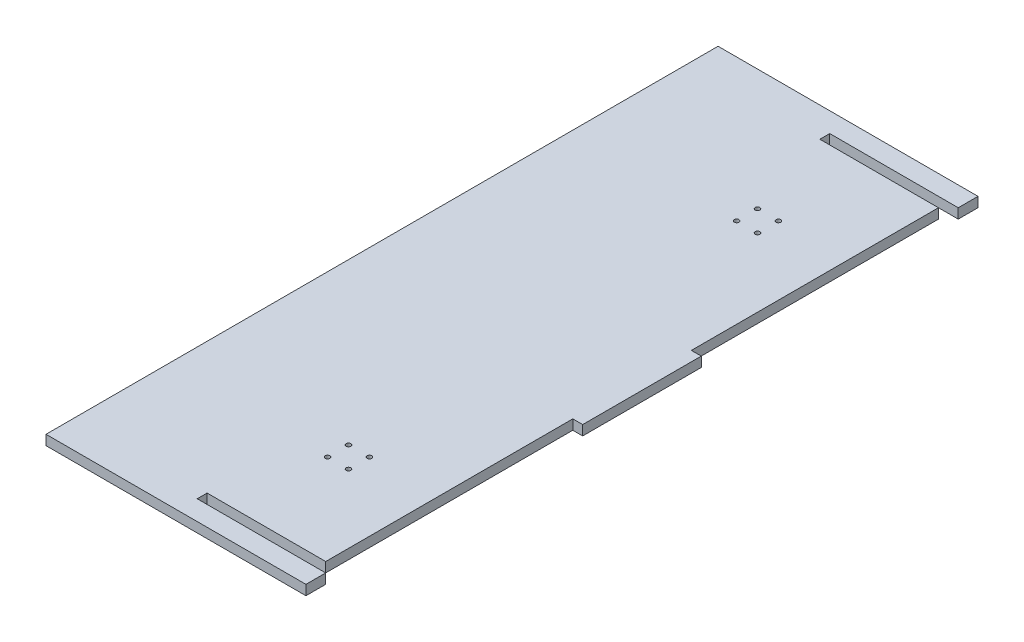
SolidWorks part; units mm, degrees
ref_plane "Front Plane" through (0, 0, 0) normal (0, 0, 1) x (1, 0, 0)
ref_plane "Top Plane" through (0, 0, 0) normal (0, 1, 0) x (1, 0, 0)
ref_plane "Right Plane" through (0, 0, 0) normal (1, 0, 0) x (0, 0, -1)
sketch "Sketch2" plane through (0, 0, 0) normal (0, 1, 0) x (1, 0, 0)
  line L1 (-83.5025, 215.9) -> (83.5025, 215.9)
  line L2 (-83.5025, 215.9) -> (-83.5025, -215.9)
  line L3 (-83.5025, -215.9) -> (83.5025, -215.9)
  line L4 (83.5025, 215.9) -> (83.5025, -215.9)
  line L5 (-83.5025, 215.9) -> (83.5025, -215.9) construction
  line L6 (-83.5025, -215.9) -> (83.5025, 215.9) construction
  point P0 (0, 0)
  dimension "D1" = 431.8
  dimension "D2" = 167.005
extrude "Boss-Extrude2" add sketch "Sketch2" along normal mid plane 6.35
sketch "Sketch3" plane through (0, 3.175, 0) normal (0, 1, 0) x (1, 0, 0)
  line L0 (83.5025, -215.9) -> (83.5025, 215.9) construction
  line L1 (83.5025, 196.85) -> (77.1525, 196.85)
  line L2 (83.5025, 196.85) -> (83.5025, -196.85)
  line L3 (83.5025, -196.85) -> (77.1525, -196.85)
  line L4 (77.1525, 196.85) -> (77.1525, -196.85)
  line L5 (83.5025, 215.9) -> (-83.5025, 215.9) construction
  point P8 (77.1525, 0)
  dimension "D1" = 6.35
  dimension "D2" = 19.05
extrude "Cut-Extrude1" cut sketch "Sketch3" against normal through all
sketch "Sketch4" plane through (0, 3.175, 0) normal (0, 1, 0) x (1, 0, 0)
  line L0 (-83.5025, 215.9) -> (-83.5025, -215.9) construction
  line L1 (-83.5025, 190.5) -> (-98.4758, 190.5)
  line L2 (-83.5025, 190.5) -> (-83.5025, -196.85)
  line L3 (-83.5025, -196.85) -> (-98.4758, -196.85)
  line L4 (-98.4758, 190.5) -> (-98.4758, -196.85)
  line L6 (83.5025, 215.9) -> (-83.5025, 215.9) construction
  line L7 (-83.5025, -215.9) -> (83.5025, -215.9) construction
  dimension "D1" = 14.9733
  dimension "D2" = 25.4
  dimension "D3" = 19.05
sketch "Sketch5" plane through (0, 3.175, 0) normal (0, 1, 0) x (1, 0, 0)
  line L1 (-32.7025, 203.2) -> (-83.5025, 203.2)
  line L2 (-32.7025, 203.2) -> (-32.7025, 196.85)
  line L3 (-32.7025, 196.85) -> (-83.5025, 196.85)
  line L4 (-83.5025, 203.2) -> (-83.5025, 196.85)
  line L5 (-83.5025, 215.9) -> (-83.5025, -215.9) construction
  line L7 (-83.5025, 215.9) -> (-83.5025, -215.9) construction
  line L8 (-83.5025, -203.2) -> (-32.7025, -203.2)
  line L9 (-83.5025, -203.2) -> (-83.5025, -196.85)
  line L10 (-83.5025, -196.85) -> (-32.7025, -196.85)
  line L11 (-32.7025, -203.2) -> (-32.7025, -196.85)
  line L13 (83.5025, 215.9) -> (-83.5025, 215.9) construction
  line L14 (-83.5025, -215.9) -> (83.5025, -215.9) construction
  dimension "D1" = 6.35
  dimension "D2" = 50.8
  dimension "D3" = 50.8
  dimension "D4" = 6.35
  dimension "D5" = 12.7
  dimension "D6" = 12.7
extrude "Cut-Extrude2" [suppressed] cut sketch "Sketch5" against normal through all
sketch "Sketch6" plane through (0, 3.175, 0) normal (0, 1, 0) x (1, 0, 0)
  line L0 (19.635, -124.6775) -> (33.07, -124.6775) construction
  line L1 (33.07, -124.6775) -> (33.07, -138.1125) construction
  line L2 (33.07, -138.1125) -> (19.635, -138.1125) construction
  line L3 (19.635, -138.1125) -> (19.635, -124.6775) construction
  line L4 (77.1525, 196.85) -> (77.1525, -196.85) construction
  circle A0 centre (19.635, -124.6775) radius 1.5
  circle A1 centre (19.635, -138.1125) radius 1.5
  circle A2 centre (33.07, -124.6775) radius 1.5
  circle A3 centre (33.07, -138.1125) radius 1.5
  point P10 (26.3525, -124.6775)
  dimension "D1" = 3
  dimension "D2" = 19
  dimension "D3" = 138.1125
  dimension "D4" = 50.8
extrude "Cut-Extrude3" cut sketch "Sketch6" against normal through all
mirror "Mirror1" about plane through (0, 0, 0) normal (0, 0, 1) of "Cut-Extrude3"
sketch "Sketch7" plane through (0, 3.175, 0) normal (0, 1, 0) x (1, 0, 0)
  line L1 (83.5025, 203.2) -> (0.9525, 203.2)
  line L2 (83.5025, 203.2) -> (83.5025, 196.85)
  line L3 (83.5025, 196.85) -> (0.9525, 196.85)
  line L4 (0.9525, 203.2) -> (0.9525, 196.85)
  line L5 (83.5025, -203.2) -> (0.9525, -203.2)
  line L6 (83.5025, -203.2) -> (83.5025, -196.85)
  line L7 (83.5025, -196.85) -> (0.9525, -196.85)
  line L8 (0.9525, -203.2) -> (0.9525, -196.85)
  dimension "D1" = 82.55
  dimension "D2" = 6.35
extrude "Cut-Extrude4" cut sketch "Sketch7" against normal through all
sketch "Sketch8" plane through (0, 3.175, 0) normal (0, 1, 0) x (1, 0, 0)
  line L0 (77.1525, 196.85) -> (77.1525, -196.85) construction
  line L1 (77.1525, 38.1) -> (83.5025, 38.1)
  line L2 (77.1525, 38.1) -> (77.1525, -38.1)
  line L3 (77.1525, -38.1) -> (83.5025, -38.1)
  line L4 (83.5025, 38.1) -> (83.5025, -38.1)
  point P6 (83.5025, 0)
  dimension "D1" = 76.2
  dimension "D2" = 6.35
extrude "Boss-Extrude3" add sketch "Sketch8" against normal up to surface (6.35 mm away) up to face at (19.635, -3.175, -139.6125)
